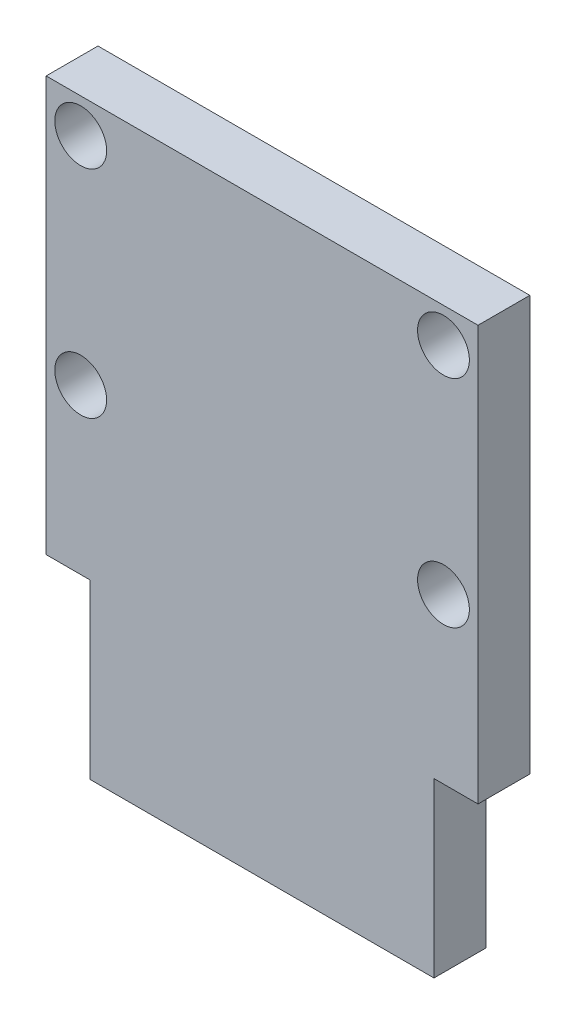
SolidWorks part; units mm, degrees
ref_plane "Front Plane" through (0, 0, 0) normal (0, 0, 1) x (1, 0, 0)
ref_plane "Top Plane" through (0, 0, 0) normal (0, 1, 0) x (1, 0, 0)
ref_plane "Right Plane" through (0, 0, 0) normal (1, 0, 0) x (0, 0, -1)
sketch "Sketch1" plane through (0, 0, 0) normal (0, 0, 1) x (1, 0, 0)
  line L0 (-996.4284, 15.75) -> (49003.5716, 15.75) construction
  line L1 (0, 0) -> (25, 0)
  line L2 (0, 0) -> (0, 24)
  line L3 (0, 24) -> (25, 24)
  line L4 (25, 0) -> (25, 24)
  line L5 (12.5, -976) -> (12.5, 49024) construction
  line L7 (2.55, 0) -> (22.45, 0)
  line L8 (2.55, 0) -> (2.55, -10)
  line L9 (2.55, -10) -> (22.45, -10)
  line L10 (22.45, 0) -> (22.45, -10)
  circle A0 centre (2, 22) radius 1.5
  circle A1 centre (23, 22) radius 1.5
  circle A2 centre (23, 9.5) radius 1.5
  circle A3 centre (2, 9.5) radius 1.5
  point P9 (12.5, -10)
  point P12 (12.5, 24)
  dimension "D3" = 3
  dimension "D1" = 25
  dimension "D2" = 24
  dimension "D4" = 21
  dimension "D5" = 12.5
  dimension "D6" = 2
  dimension "D7" = 19.9
  dimension "D8" = 10
extrude "Boss-Extrude1" add sketch "Sketch1" along normal blind 3 contours L1 L4 L3 L2 A1 A0 A2 A3 | L10 L1 L8 L9
